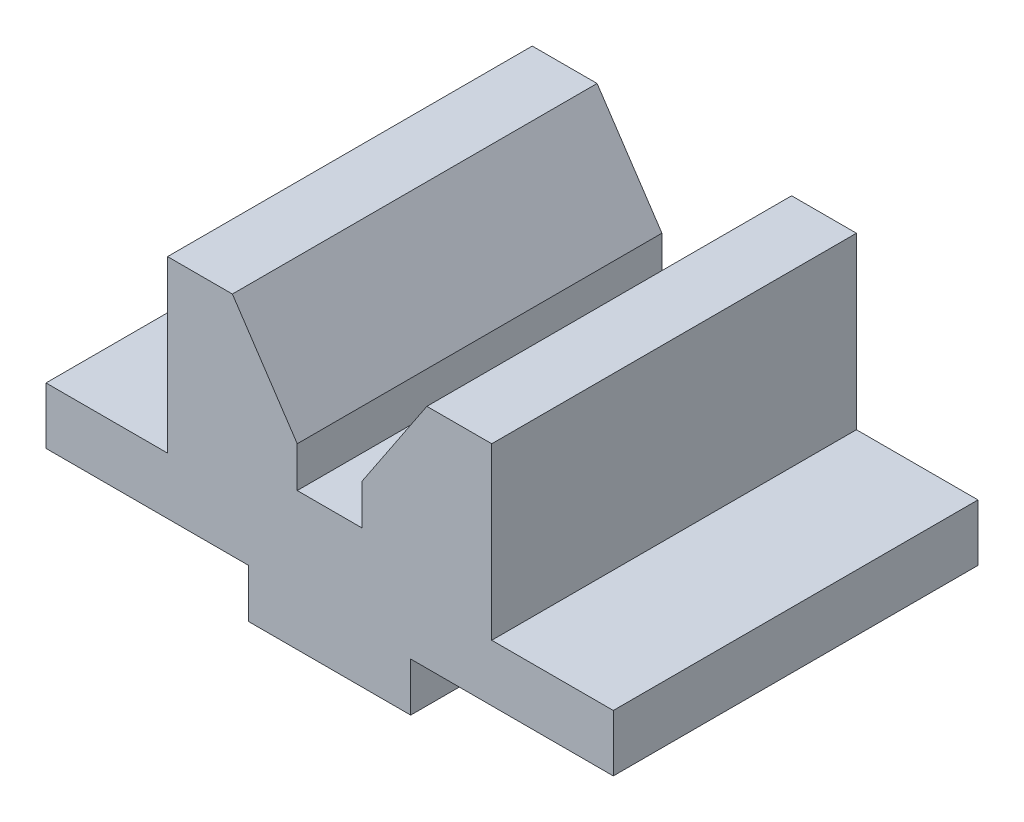
SolidWorks part; units mm, degrees
ref_plane "Front Plane" through (0, 0, 0) normal (0, 0, 1) x (1, 0, 0)
ref_plane "Top Plane" through (0, 0, 0) normal (0, 1, 0) x (1, 0, 0)
ref_plane "Right Plane" through (0, 0, 0) normal (1, 0, 0) x (0, 0, -1)
sketch "Sketch1" plane through (0, 0, 0) normal (0, 0, 1) x (1, 0, 0)
  line L0 (-10, 0) -> (10, 0)
  line L2 (10, 0) -> (10, 6)
  line L3 (10, 6) -> (35, 6)
  line L4 (35, 6) -> (35, 13)
  line L5 (35, 13) -> (20, 13)
  line L6 (20, 13) -> (20, 34)
  line L7 (20, 34) -> (12, 34)
  line L10 (-20, 34) -> (-12, 34)
  line L11 (-20, 13) -> (-20, 34)
  line L12 (-35, 13) -> (-20, 13)
  line L13 (-35, 6) -> (-35, 13)
  line L14 (-10, 6) -> (-35, 6)
  line L15 (-10, 0) -> (-10, 6)
  line L17 (-12, 34) -> (-4, 22)
  line L18 (12, 34) -> (4, 22)
  line L20 (-4, 22) -> (-4, 17)
  line L21 (4, 22) -> (4, 17)
  line L22 (-4, 17) -> (4, 17)
extrude "Boss-Extrude1" add sketch "Sketch1" along normal blind 45
